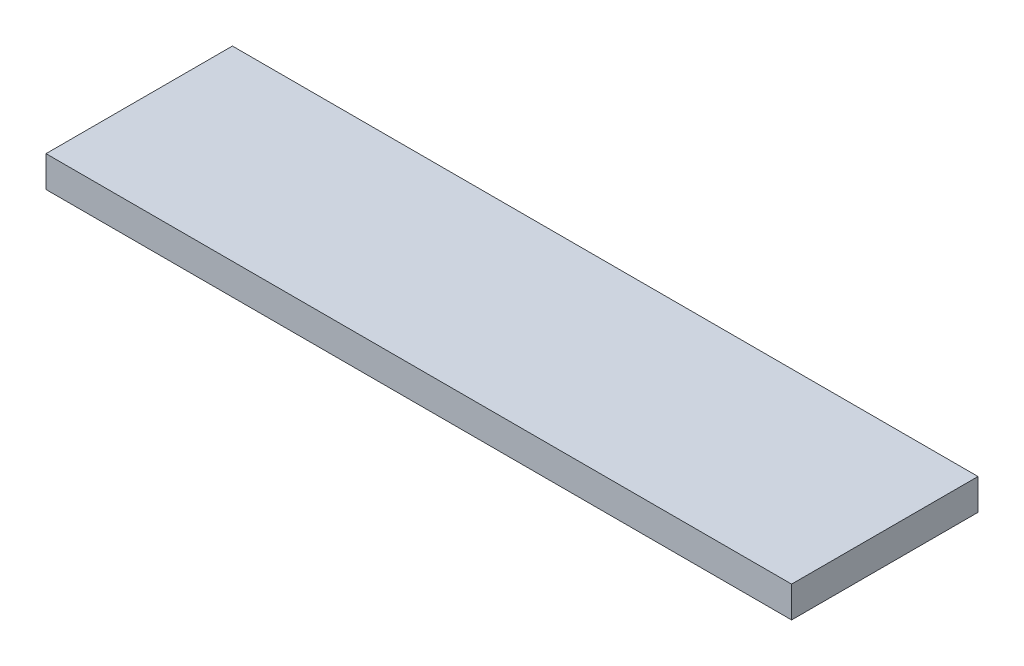
SolidWorks part; units mm, degrees
ref_plane "Front Plane" through (0, 0, 0) normal (0, 0, 1) x (1, 0, 0)
ref_plane "Top Plane" through (0, 0, 0) normal (0, 1, 0) x (1, 0, 0)
ref_plane "Right Plane" through (0, 0, 0) normal (1, 0, 0) x (0, 0, -1)
sketch "Sketch1" plane through (0, 0, 0) normal (0, 1, 0) x (1, 0, 0)
  line L1 (-180, -45) -> (180, -45)
  line L2 (-180, -45) -> (-180, 45)
  line L3 (-180, 45) -> (180, 45)
  line L4 (180, -45) -> (180, 45)
  line L5 (-180, -45) -> (180, 45) construction
  line L6 (-180, 45) -> (180, -45) construction
  point P0 (0, 0)
  dimension "D1" = 90
  dimension "D2" = 360
extrude "Boss-Extrude1" add sketch "Sketch1" along normal blind 15
